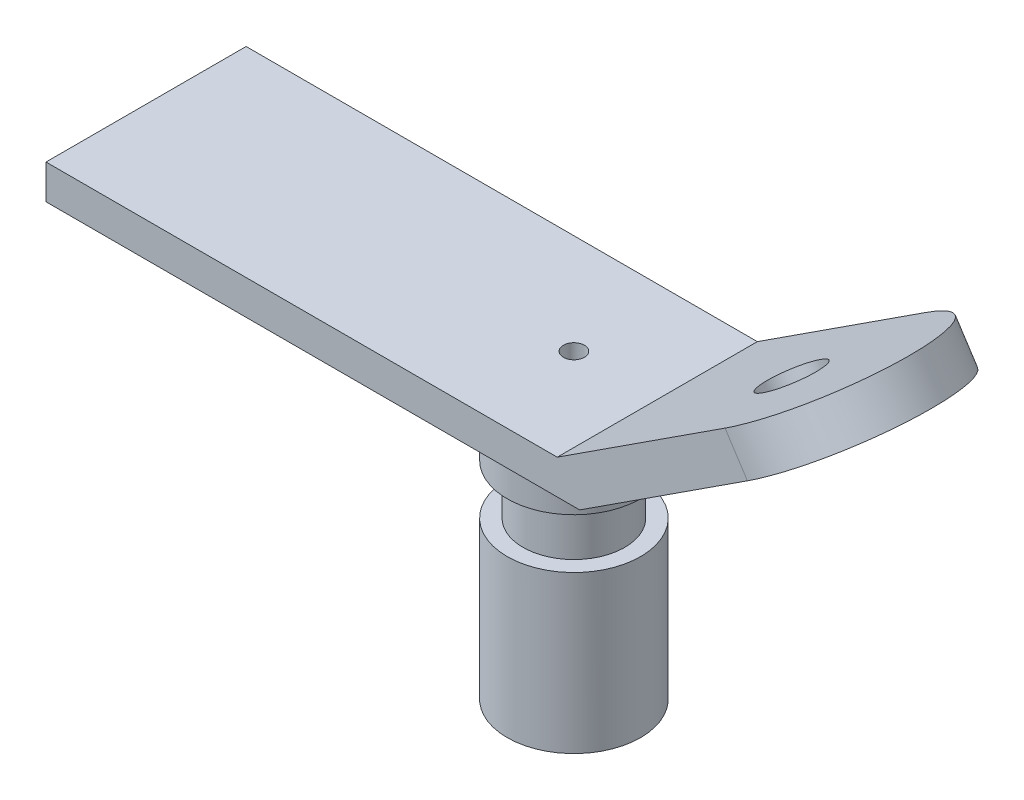
SolidWorks part; units mm, degrees
material "Custom Plastic"
ref_plane "Front Plane" through (0, 0, 0) normal (0, 0, 1) x (1, 0, 0)
ref_plane "Top Plane" through (0, 0, 0) normal (0, 1, 0) x (1, 0, 0)
ref_plane "Right Plane" through (0, 0, 0) normal (1, 0, 0) x (0, 0, -1)
other "Configuration Table"
sketch "Sketch1" plane through (0, 0, 0) normal (0, 0, 1) x (1, 0, 0)
  line L0 (0, 0) -> (127.7788, 83.0562)
  line L1 (127.7788, 83.0562) -> (119.2464, 96.1831)
  line L2 (119.2464, 96.1831) -> (-8.5324, 13.1268)
  line L3 (-8.5324, 13.1268) -> (0, 0)
  line L4 (0, 0) -> (-203.2, 0)
  line L5 (-203.2, 0) -> (-203.2, 13.1268)
  line L6 (-203.2, 13.1268) -> (-8.5324, 13.1268)
  dimension "D1" = 203.2
  dimension "D2" = 152.4
extrude "Boss-Extrude1" add sketch "Sketch1" along normal blind 76.2 contours L6 L5 L4 L3 | L2 L3 L0 L1
sketch "Sketch2" plane through (0, 0, 0) normal (0, -1, 0) x (1, 0, 0)
  line L0 (-14.8824, 76.2) -> (-14.8824, 0) construction
  line L1 (0, 76.2) -> (0, 0) construction
  line L2 (0, 0) -> (-203.2, 0) construction
  line L3 (0, 76.2) -> (-203.2, 76.2) construction
  line L4 (-203.2, 38.1) -> (134.5551, 38.1) construction
  line L5 (-203.2, 76.2) -> (-203.2, 0) construction
  line L6 (-8.5324, 76.2) -> (-8.5324, 0) construction
  circle A0 centre (-40.2824, 38.1) radius 25.4
  circle A1 centre (-40.2824, 38.1) radius 4.0005
  point P7 (0, 38.1)
  dimension "D2" = 8.001
  dimension "D3" = 50.8
  dimension "D1" = 38.1
  dimension "D4" = 6.35
extrude "Boss-Extrude2" add sketch "Sketch2" along normal blind 101.6
ref_plane "Plane1" through (0, 0, 38.1) normal (0, 0, 1) x (1, 0, 0)
sketch "Sketch4" plane through (0, 0, 38.1) normal (0, 0, 1) x (1, 0, 0)
  line L0 (-65.6824, -101.6) -> (-14.8824, -101.6) construction
  line L1 (-65.9926, -22.8346) -> (-59.6426, -22.8346)
  line L2 (-65.9926, -22.8346) -> (-65.9926, -41.8846)
  line L3 (-65.9926, -41.8846) -> (-59.6426, -41.8846)
  line L4 (-59.6426, -22.8346) -> (-59.6426, -41.8846)
  line L5 (-40.2824, -101.6) -> (-40.2824, 26.8641) construction
  dimension "D1" = 78.7654
  dimension "D2" = 6.35
  dimension "D3" = 19.05
revolve "Cut-Revolve1" cut sketch "Sketch4" angle 360 about L5
sketch "Sketch5" plane through (0, 0, 0) normal (0, -1, 0) x (1, 0, 0)
  circle A0 centre (-40.2824, 38.1) radius 4.0005 construction
  circle A1 centre (-40.2824, 38.1) radius 4.0005
extrude "Cut-Extrude1" cut sketch "Sketch5" against normal through all
sketch "Sketch7" plane through (-8.5324, 13.1268, 0) normal (-0.545, 0.8384, 0) x (0.8384, 0.545, 0)
  line L0 (0, -38.1) -> (187.0308, -38.1) construction
  line L1 (0, -76.2) -> (0, 0) construction
  circle A0 centre (61.0108, -38.1) radius 57.15 construction
  circle A1 centre (61.0108, -38.1) radius 10.9982
  dimension "D1" = 114.3
  dimension "D3" = 21.9964
  dimension "D2" = 61.0108
extrude "Cut-Extrude2" cut sketch "Sketch7" against normal through all
sketch "Sketch8" plane through (-8.5324, 13.1268, 0) normal (-0.545, 0.8384, 0) x (0.8384, 0.545, 0)
  line L1 (152.4, 0) -> (0, 0) construction
  line L3 (152.4, -76.2) -> (0, -76.2) construction
  line L4 (76.2, 0) -> (152.4, 0)
  line L5 (152.4, 0) -> (152.4, -76.2)
  line L6 (152.4, -76.2) -> (76.2, -76.2)
  line L7 (0, -76.2) -> (0, 0) construction
  arc A0 (76.2, 0) -> (76.2, -76.2) centre (76.2, -38.1) cw
  dimension "D1" = 38.1
  dimension "D2" = 76.2
extrude "Cut-Extrude3" cut sketch "Sketch8" against normal through all
